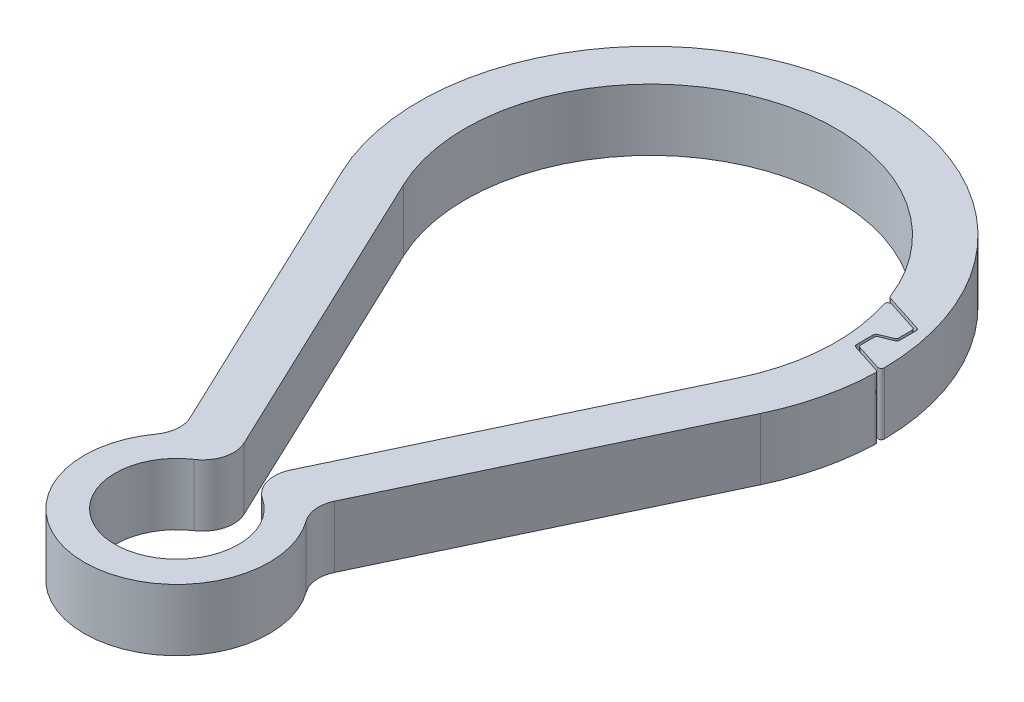
SolidWorks part; units mm, degrees
ref_plane "Front Plane" through (0, 0, 0) normal (0, 0, 1) x (1, 0, 0)
ref_plane "Top Plane" through (0, 0, 0) normal (0, 1, 0) x (1, 0, 0)
ref_plane "Right Plane" through (0, 0, 0) normal (1, 0, 0) x (0, 0, -1)
sketch "Sketch1" plane through (0, 0, 0) normal (0, 1, 0) x (1, 0, 0)
  line L0 (-33.88, 60.6026) -> (-7.2302, 4.4341)
  line L1 (0, 76.6773) -> (0, -10) construction
  line L2 (-27.104, 63.8175) -> (-1.4446, 9.7363)
  line L3 (27.104, 63.8175) -> (1.4446, 9.7363)
  line L4 (33.88, 60.6026) -> (7.2302, 4.4341)
  circle A0 centre (0, 0) radius 10
  circle A1 centre (0, 0) radius 15
  circle A2 centre (0, 76.6773) radius 30
  circle A3 centre (0, 76.6773) radius 37.5
  dimension "D1" = 30
  dimension "D2" = 20
  dimension "D3" = 60
  dimension "D4" = 75
extrude "Boss-Extrude1" add sketch "Sketch1" along normal blind 10 contours L3 A3 L2 A2 | A3 L3 A1 L4 | A3 L0 A1 L2 | L0 A1 L4 A0 | L2 A1 L0 A0 | L4 A1 L3 A0
fillet "Fillet1" radius 5 4 edges at (10.3002, 5, -10.9044) (-10.3002, 5, -10.9044) (1.5149, 5, -9.8846) (-1.5149, 5, -9.8846)
sketch "Sketch2" plane through (0, 10, 0) normal (0, 1, 0) x (1, 0, 0)
  line L0 (21.9387, 89.0972) -> (34.6831, 85.0056) construction
  line L1 (34.6831, 85.0056) -> (34.6831, 81.944) construction
  line L2 (34.6831, 81.944) -> (32.1831, 80.9251) construction
  line L3 (32.1831, 80.9251) -> (32.1831, 77.8635) construction
  line L4 (32.1831, 77.8635) -> (46.194, 73.3653) construction
  line L5 (29.6202, 81.4358) -> (37.1969, 81.4358) construction
  line L6 (33.4331, 81.4345) -> (33.4331, 88.4063) construction
  line L7 (33.4331, 81.4345) -> (33.4331, 74.3302) construction
  line L8 (21.8776, 88.9067) -> (34.1359, 84.9712)
  line L9 (34.4831, 84.4951) -> (34.4831, 82.4146)
  line L10 (34.1718, 81.9516) -> (32.2943, 81.1864)
  line L11 (31.9831, 80.7234) -> (31.9831, 78.0823)
  line L12 (32.3302, 77.6062) -> (46.1328, 73.1749)
  line L13 (21.9999, 89.2876) -> (34.5359, 85.2629)
  line L14 (34.8831, 84.7868) -> (34.8831, 82.1457)
  line L15 (34.5718, 81.6827) -> (32.6943, 80.9175)
  line L16 (32.3831, 80.4545) -> (32.3831, 78.374)
  line L17 (32.7302, 77.8979) -> (46.2551, 73.5557)
  line L18 (21.8776, 88.9067) -> (21.9999, 89.2876)
  line L19 (46.1328, 73.1749) -> (46.2551, 73.5557)
  line L20 (32.3831, 80.7906) -> (32.3831, 78.0094) construction
  line L21 (32.3831, 78.0094) -> (46.2551, 73.5557) construction
  line L22 (31.9831, 81.0595) -> (31.9831, 77.7177) construction
  line L23 (31.9831, 77.7177) -> (46.1328, 73.1749) construction
  line L24 (34.8831, 81.8095) -> (32.3831, 80.7906) construction
  line L25 (34.4831, 82.0785) -> (31.9831, 81.0595) construction
  line L26 (34.8831, 85.1514) -> (34.8831, 81.8095) construction
  line L27 (34.4831, 84.8597) -> (34.4831, 82.0785) construction
  line L28 (21.9999, 89.2876) -> (34.8831, 85.1514) construction
  line L29 (21.8776, 88.9067) -> (34.4831, 84.8597) construction
  arc A0 (27.104, 63.8175) -> (-27.104, 63.8175) centre (0, 76.6773) ccw construction
  arc A1 (33.88, 60.6026) -> (-33.88, 60.6026) centre (0, 76.6773) ccw construction
  arc A2 (32.3831, 78.374) -> (32.7302, 77.8979) centre (32.8831, 78.374) ccw
  arc A3 (31.9831, 78.0823) -> (32.3302, 77.6062) centre (32.4831, 78.0823) ccw
  arc A4 (32.6943, 80.9175) -> (32.3831, 80.4545) centre (32.8831, 80.4545) ccw
  arc A5 (32.2943, 81.1864) -> (31.9831, 80.7234) centre (32.4831, 80.7234) ccw
  arc A6 (34.8831, 82.1457) -> (34.5718, 81.6827) centre (34.3831, 82.1457) cw
  arc A7 (34.4831, 82.4146) -> (34.1718, 81.9516) centre (33.9831, 82.4146) cw
  arc A8 (34.5359, 85.2629) -> (34.8831, 84.7868) centre (34.3831, 84.7868) cw
  arc A9 (34.1359, 84.9712) -> (34.4831, 84.4951) centre (33.9831, 84.4951) cw
  dimension "D4" = 0.5
  dimension "D1" = 2.5
  dimension "D2" = 0.2
  dimension "D3" = 0.2
extrude "Cut-Extrude1" cut sketch "Sketch2" against normal through all
fillet "Fillet2" radius 0.5 4 edges at (37.4929, 5, -75.9487) (28.2146, 5, -86.8722) (28.0377, 5, -87.3491) (37.4987, 5, -76.367)
